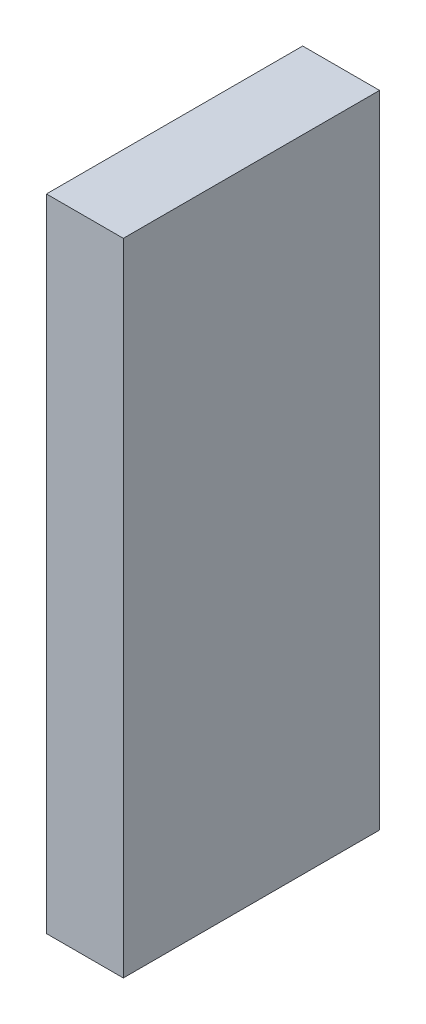
SolidWorks part; units mm, degrees
ref_plane "Front Plane" through (0, 0, 0) normal (0, 0, 1) x (1, 0, 0)
ref_plane "Top Plane" through (0, 0, 0) normal (0, 1, 0) x (1, 0, 0)
ref_plane "Right Plane" through (0, 0, 0) normal (1, 0, 0) x (0, 0, -1)
sketch "Sketch1" plane through (0, 0, 0) normal (0, 1, 0) x (1, 0, 0)
  line L1 (-6, 20) -> (6, 20)
  line L2 (-6, 20) -> (-6, -20)
  line L3 (-6, -20) -> (6, -20)
  line L4 (6, 20) -> (6, -20)
  line L5 (-6, 20) -> (6, -20) construction
  line L6 (-6, -20) -> (6, 20) construction
  point P0 (0, 0)
  dimension "D1" = 40
  dimension "D2" = 12
extrude "Boss-Extrude1" add sketch "Sketch1" along normal mid plane 100
scale "25% Scale" bodies to scale 101 scale about centroid uniform scaling yes scale factor 0.25
